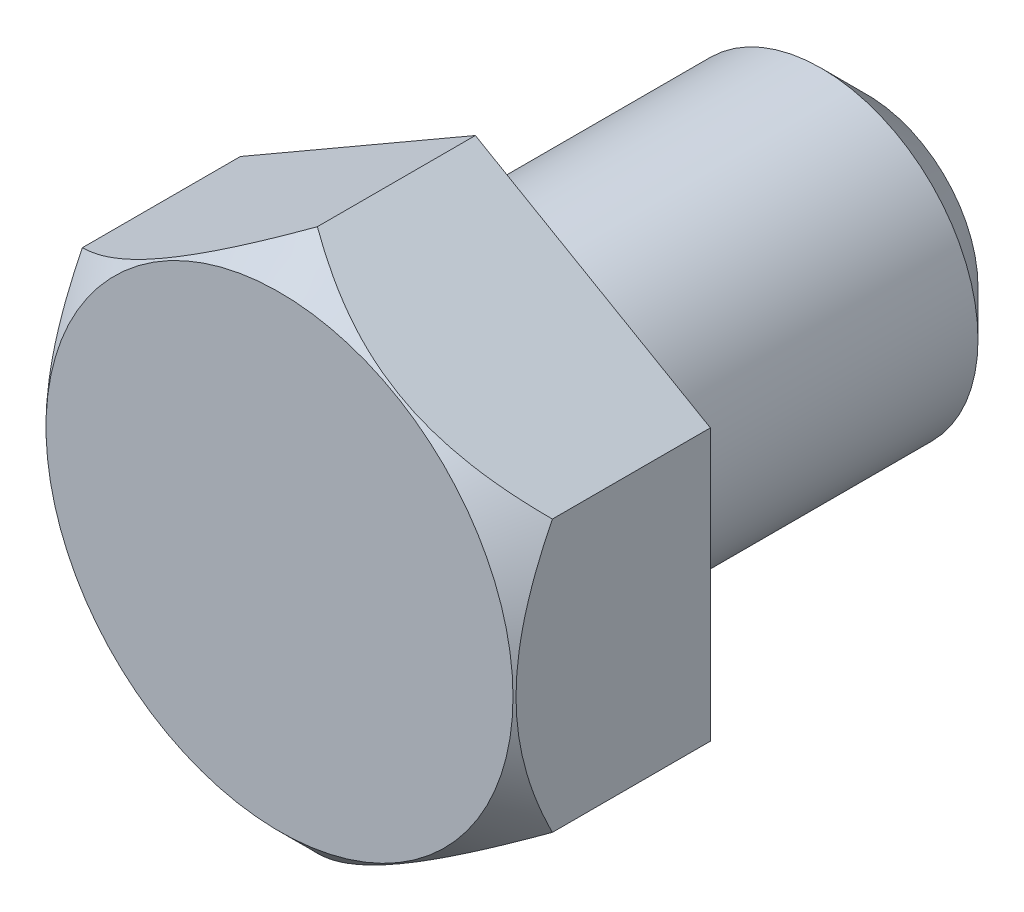
SolidWorks part; units mm, degrees
ref_plane "Спереди" through (0, 0, 0) normal (0, 0, 1) x (1, 0, 0)
ref_plane "Сверху" through (0, 0, 0) normal (0, 1, 0) x (1, 0, 0)
ref_plane "Справа" through (0, 0, 0) normal (1, 0, 0) x (0, 0, -1)
sketch "Эскиз1" plane through (0, 0, 0) normal (0, 0, 1) x (1, 0, 0)
  line L0 (0, 4.93) -> (0, -5.4719) construction
  line L1 (-5.0323, 0) -> (5.1026, 0) construction
  line L3 (0, 10.3923) -> (-9, 5.1962)
  line L4 (-9, 5.1962) -> (-9, -5.1962)
  line L5 (-9, -5.1962) -> (0, -10.3923)
  line L6 (0, -10.3923) -> (9, -5.1962)
  line L7 (9, -5.1962) -> (9, 5.1962)
  line L8 (9, 5.1962) -> (0, 10.3923)
  circle A0 centre (0, 0) radius 9 construction
extrude "Вытянуть1" add sketch "Эскиз1" along normal blind 7.5
sketch "Эскиз2" plane through (0, 0, 0) normal (0, 0, -1) x (-1, 0, 0)
  circle A0 centre (0, 0) radius 6
extrude "Вытянуть2" add sketch "Эскиз2" along normal blind 15
ref_axis "Ось4" through (0, 0, -2.5347) along (0, 0, -1)
sketch "Эскиз15" plane through (0, 0, 0) normal (1, 0, 0) x (0, 0, -1)
  line L0 (-7.5, 10.3923) -> (-7.5, 8.9423)
  line L1 (-7.5, 5.1962) -> (-7.5, 10.3923) construction
  line L2 (-7.5, 8.9423) -> (-6.05, 10.3923)
  line L3 (-7.5, 10.3923) -> (0, 10.3923) construction
  line L4 (-6.05, 10.3923) -> (-7.5, 10.3923)
revolve "Вырез-Повернуть1" cut sketch "Эскиз15" angle 360 about axis through (0, 0, -2.5347) along (0, 0, -1)
ref_plane "Плоскость1" through (0, 0, 0) normal (0, -1, 0) x (1, 0, 0)
chamfer "Фаска1" distance 1.75 angle 45 1 edges at (-6, 0, -15)
